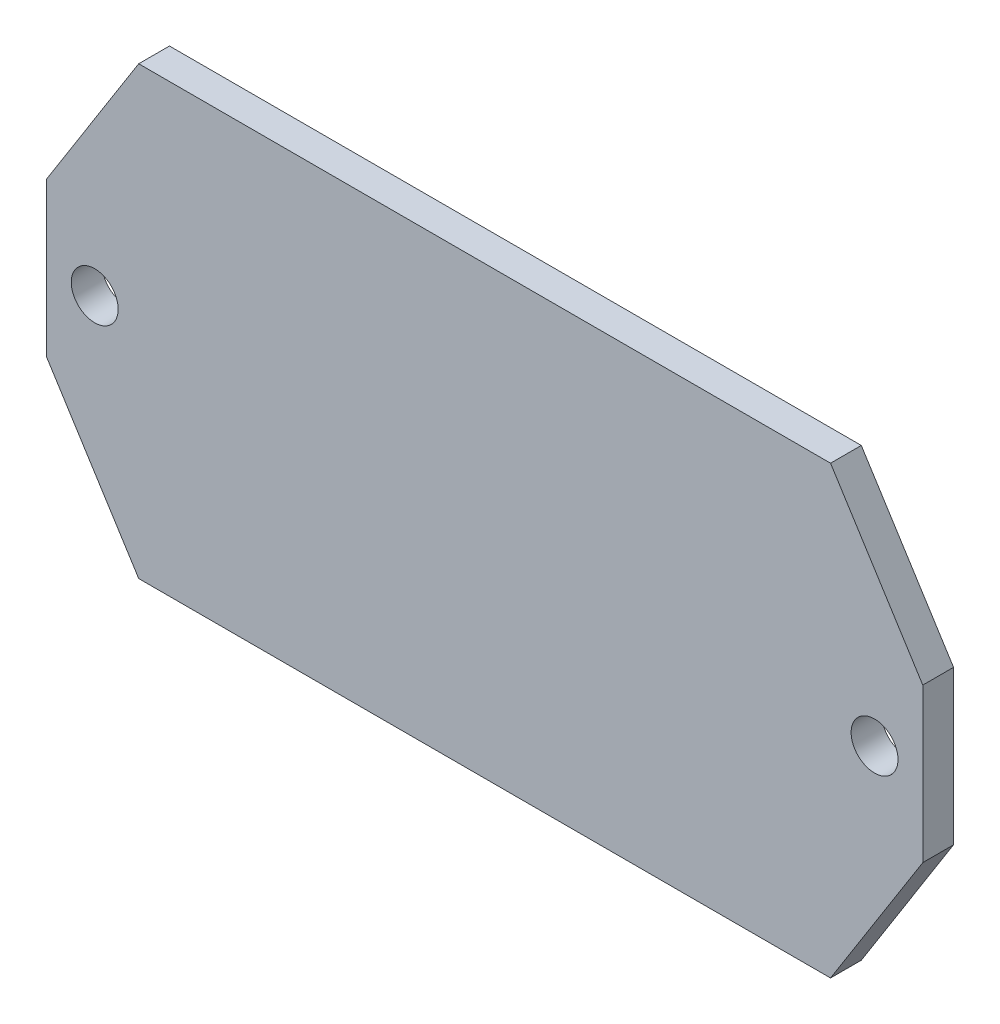
SolidWorks part; units mm, degrees
material "PC High Viscosity"
ref_plane "前视基准面" through (0, 0, 0) normal (0, 0, 1) x (1, 0, 0)
ref_plane "上视基准面" through (0, 0, 0) normal (0, 1, 0) x (1, 0, 0)
ref_plane "右视基准面" through (0, 0, 0) normal (1, 0, 0) x (0, 0, -1)
other "Configuration Table"
sketch "草图1" plane through (0, 0, 0) normal (0, 0, 1) x (1, 0, 0)
  line L1 (-28.5, -14.5) -> (28.5, -14.5)
  line L2 (-28.5, -14.5) -> (-28.5, 14.5)
  line L3 (-28.5, 14.5) -> (28.5, 14.5)
  line L4 (28.5, -14.5) -> (28.5, 14.5)
  line L5 (-28.5, -14.5) -> (28.5, 14.5) construction
  line L6 (-28.5, 14.5) -> (28.5, -14.5) construction
  point P0 (0, 0)
  dimension "D1" = 29
  dimension "D2" = 57
extrude "凸台-拉伸1" add sketch "草图1" along normal blind 2
sketch "草图2" plane through (0, 0, 2) normal (0, 0, 1) x (1, 0, 0)
  line L0 (22.5, 14.5) -> (28.5, 5)
  line L1 (28.5, 14.5) -> (-28.5, 14.5) construction
  line L2 (28.5, -14.5) -> (28.5, 14.5) construction
  line L3 (28.5, 5) -> (28.5, 14.5)
  line L4 (28.5, 14.5) -> (22.5, 14.5)
  line L5 (0, 0) -> (38.7786, 0) construction
  line L6 (28.5, -14.5) -> (22.5, -14.5)
  line L7 (28.5, -5) -> (28.5, -14.5)
  line L8 (22.5, -14.5) -> (28.5, -5)
  dimension "D1" = 6
  dimension "D2" = 5
extrude "切除-拉伸1" cut sketch "草图2" against normal blind 2
mirror "镜向1" about plane through (0, 0, 0) normal (1, 0, 0) of "切除-拉伸1"
sketch "草图3" plane through (0, 0, 2) normal (0, 0, 1) x (1, 0, 0)
  line L0 (0, 0) -> (0, 14.5) construction
  line L1 (22.5, 14.5) -> (-22.5, 14.5) construction
  circle A0 centre (25.3627, 0) radius 1.25 construction
  circle A1 centre (25.3627, 0) radius 1.25 construction
  circle A2 centre (25.3627, 0) radius 1.525
  circle A3 centre (-25.3627, 0) radius 1.25 construction
  circle A4 centre (-25.3627, 0) radius 1.525
  dimension "D1" = 3.05
extrude "切除-拉伸2" cut sketch "草图3" against normal blind 2
